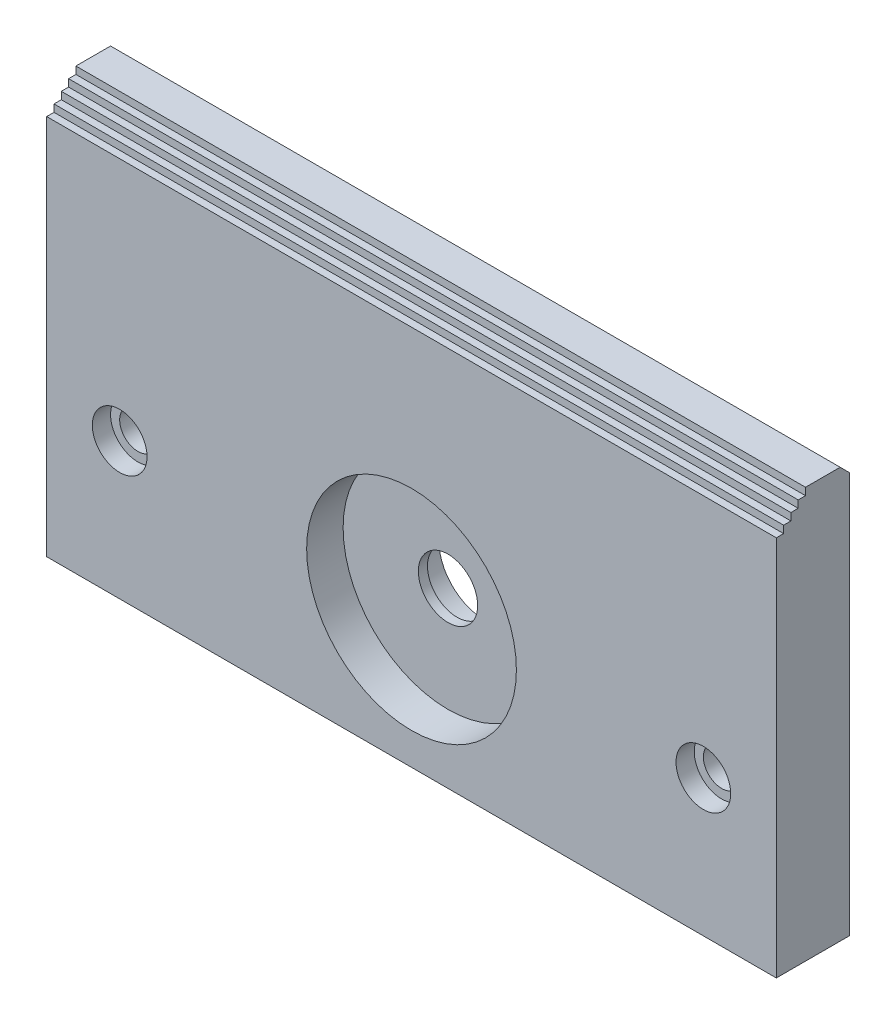
SolidWorks part; units mm, degrees
ref_plane "前视基准面" through (0, 0, 0) normal (0, 0, 1) x (1, 0, 0)
ref_plane "上视基准面" through (0, 0, 0) normal (0, 1, 0) x (1, 0, 0)
ref_plane "右视基准面" through (0, 0, 0) normal (1, 0, 0) x (0, 0, -1)
other "Configuration Table"
ref_plane "基准面1" through (0, 0, 8) normal (0, 0, 1) x (1, 0, 0)
sketch "草图1" plane through (0, 0, 8) normal (0, 0, 1) x (1, 0, 0)
  line L0 (80, -19.1667) -> (80, 40.8333)
  line L1 (80, 40.8333) -> (0, 40.8333)
  line L2 (0, 40.8333) -> (0, -19.1667)
  line L3 (0, -19.1667) -> (80, -19.1667)
  dimension "D1" = 80
  dimension "D2" = 60
extrude "凸台-拉伸1" add sketch "草图1" against normal blind 8
hole_wizard "M3.5 六角头机械螺钉的柱形沉头孔1" positions "草图13" profile "草图12" counterbore size "M3.5" standard "ANSI Metric" end condition through all
sketch "草图13" plane through (0, 0, 8) normal (0, 0, 1) x (1, 0, 0)
  line L1 (0, 10.8333) -> (80, 10.8333) construction
  line L2 (0, 40.8333) -> (0, -19.1667) construction
  line L3 (80, -19.1667) -> (80, 40.8333) construction
  point P0 (8, 10.8333)
  point P1 (72, 10.8333)
  dimension "D1" = 8
  dimension "D2" = 8
sketch "草图12" plane through (8, 10.8333, 8) normal (1, 0, 0) x (0, -1, 0)
  line L0 (0, 0) -> (0, 8)
  line L1 (0, 8) -> (2, 8)
  line L3 (2, 8) -> (2, 2)
  line L4 (2, 2) -> (3, 2)
  line L5 (3, 2) -> (3, 0)
  line L7 (3, 0) -> (0, 0)
  line L11 (0, -6.35) -> (0, 107.95) construction
  dimension "通孔孔直径" = 4
  dimension "通孔孔深度" = 8
  dimension "柱形沉头孔直径" = 6
  dimension "柱形沉头孔深度" = 2
sketch "草图14" plane through (0, 0, 8) normal (0, 0, 1) x (1, 0, 0)
  line L0 (40, 40.8333) -> (40, -19.1667) construction
  line L1 (80, 40.8333) -> (0, 40.8333) construction
  line L2 (0, -19.1667) -> (80, -19.1667) construction
  line L3 (0, 40.8333) -> (0, -19.1667) construction
  line L4 (0, 38.8333) -> (80, 38.8333)
  line L5 (0, 38.8333) -> (0, 36.8333)
  line L6 (0, 36.8333) -> (80, 36.8333)
  line L7 (40, 38.8333) -> (40, 36.8333)
  line L8 (80, -19.1667) -> (80, 40.8333) construction
  line L9 (15, 40.8333) -> (31, 24.8333)
  line L10 (6, 40.8333) -> (8, 40.8333)
  line L11 (6, 40.8333) -> (6, 24.8333)
  line L12 (6, 24.8333) -> (8, 24.8333)
  line L13 (8, 40.8333) -> (8, 24.8333)
  line L18 (39, 40.8333) -> (41, 40.8333)
  line L19 (39, 40.8333) -> (39, 24.8333)
  line L20 (39, 24.8333) -> (41, 24.8333)
  line L21 (40, 40.8333) -> (40, 24.8333)
  line L22 (31, 24.8333) -> (32.4142, 26.2475)
  line L23 (32.4142, 26.2475) -> (16.4142, 42.2475)
  line L24 (16.4142, 42.2475) -> (15, 40.8333)
  line L25 (0, 24.8333) -> (80, 24.8333) construction
  line L26 (74, 24.8333) -> (72, 24.8333)
  line L27 (72, 40.8333) -> (72, 24.8333)
  line L28 (74, 40.8333) -> (72, 40.8333)
  line L29 (74, 40.8333) -> (74, 24.8333)
  line L30 (47.5858, 26.2475) -> (63.5858, 42.2475)
  line L31 (49, 24.8333) -> (47.5858, 26.2475)
  line L32 (65, 40.8333) -> (49, 24.8333)
  line L33 (63.5858, 42.2475) -> (65, 40.8333)
  line L34 (41, 40.8333) -> (41, 24.8333)
  line L35 (80, 38.8333) -> (80, 36.8333)
  dimension "D1" = 2
  dimension "D2" = 2
  dimension "D3" = 6
  dimension "D4" = 2
  dimension "D5" = 16
  dimension "D6" = 2
  dimension "D7" = 1
  dimension "D8" = 7
  dimension "D9" = 45
extrude "切除-拉伸1" cut sketch "草图14" against normal blind 1 contours L4 L35 L6 L5 | L13 L12 L11 L10 | L9 L22 L23 L24 | L19 L20 L34 L18 | L30 L33 L32 L31 | L27 L26 L29 L28
sketch "草图15" plane through (0, 0, 8) normal (0, 0, 1) x (1, 0, 0)
  line L0 (40, 40.8333) -> (40, -19.1667) construction
  line L1 (39, 40.8333) -> (41, 40.8333) construction
  line L2 (0, -19.1667) -> (80, -19.1667) construction
  circle A0 centre (40, 10.8333) radius 3.25
  point P9 (40, 10.8333)
  dimension "D1" = 6.5
extrude "切除-拉伸2" cut sketch "草图15" against normal up to next
sketch "草图17" plane through (0, 0, 8) normal (0, 0, 1) x (1, 0, 0)
  circle A0 centre (40, 10.8333) radius 11.5
  dimension "D1" = 23
extrude "切除-拉伸4" cut sketch "草图17" against normal blind 4
sketch "草图18" plane through (0, 0, 0) normal (0, 0, -1) x (-1, 0, 0)
  circle A0 centre (-40, 10.8333) radius 5
  dimension "D1" = 10
extrude "切除-拉伸5" cut sketch "草图18" against normal blind 3
chamfer "倒角1" distance 1.5 angle 45 2 edges at (74, 10.8333, 0) (10, 10.8333, 0)
chamfer "倒角2" distance 1 angle 45 1 edges at (40, 40.8333, 0)
sketch "草图20" plane through (0, 0, 8) normal (0, 0, 1) x (1, 0, 0)
  line L0 (80, -19.1667) -> (80, 36.8333) construction
  line L1 (0, -19.1667) -> (80, -19.1667)
  line L2 (0, -19.1667) -> (0, -13.1667)
  line L3 (0, -13.1667) -> (80, -13.1667)
  line L4 (80, -19.1667) -> (80, -13.1667)
  dimension "D1" = 6
extrude "切除-拉伸6" cut sketch "草图20" against normal blind 1
sketch "草图21" plane through (0, 0, 7) normal (0, 0, 1) x (1, 0, 0)
  line L0 (80, -19.1667) -> (80, -13.1667) construction
  line L1 (0, -19.1667) -> (80, -19.1667)
  line L2 (0, -19.1667) -> (0, -15.1667)
  line L3 (0, -15.1667) -> (80, -15.1667)
  line L4 (80, -19.1667) -> (80, -15.1667)
  dimension "D1" = 4
extrude "切除-拉伸7" cut sketch "草图21" against normal blind 1
sketch "草图22" plane through (0, 0, 6) normal (0, 0, 1) x (1, 0, 0)
  line L1 (0, -19.1667) -> (80, -19.1667)
  line L2 (0, -19.1667) -> (0, -17.1667)
  line L3 (0, -17.1667) -> (80, -17.1667)
  line L4 (80, -19.1667) -> (80, -17.1667)
  dimension "D1" = 2
extrude "切除-拉伸8" cut sketch "草图22" against normal blind 1
sketch "草图23" plane through (0, 0, 8) normal (0, 0, 1) x (1, 0, 0)
  line L0 (6, 24.8333) -> (8, 24.8333) construction
  line L1 (31, 24.8333) -> (32.4142, 26.2475) construction
  line L2 (39, 24.8333) -> (41, 24.8333) construction
  line L3 (49, 24.8333) -> (47.5858, 26.2475) construction
  line L4 (74, 24.8333) -> (72, 24.8333) construction
  circle A0 centre (7, 24.8333) radius 1
  circle A1 centre (31.7071, 25.5404) radius 1
  circle A2 centre (40, 24.8333) radius 1
  circle A3 centre (48.2929, 25.5404) radius 1
  circle A4 centre (73, 24.8333) radius 1
extrude "切除-拉伸9" cut sketch "草图23" against normal up to surface (1 mm away) up to face at (40, 35.6249, 7)
sketch "草图24" plane through (0, 0, 8) normal (0, 0, 1) x (1, 0, 0)
  line L0 (0, 36.8333) -> (0, -13.1667) construction
  line L1 (0, -4.1667) -> (80, -4.1667)
  line L2 (0, -4.1667) -> (0, -19.1667)
  line L3 (0, -19.1667) -> (80, -19.1667)
  line L4 (80, -4.1667) -> (80, -19.1667)
  dimension "D1" = 15
extrude "切除-拉伸10" cut sketch "草图24" against normal up to next
sketch "草图25" plane through (0, 0, 8) normal (0, 0, 1) x (1, 0, 0)
  line L0 (80, -4.1667) -> (80, 36.8333) construction
  line L1 (0, 40.8333) -> (80, 40.8333)
  line L2 (0, 40.8333) -> (0, 22.8333)
  line L3 (0, 22.8333) -> (80, 22.8333)
  line L4 (80, 40.8333) -> (80, 22.8333)
  line L5 (0, 36.8333) -> (0, -4.1667) construction
  dimension "D1" = 18
extrude "凸台-拉伸2" add sketch "草图25" against normal blind 3
sketch "草图26" plane through (0, 0, 0) normal (-1, 0, 0) x (0, 0, 1)
  line L0 (4.8, 40.8333) -> (4.8, 40.0333)
  line L1 (1, 40.8333) -> (8, 40.8333) construction
  line L2 (4.8, 40.0333) -> (5.6, 40.0333)
  line L3 (5.6, 40.0333) -> (5.6, 39.2333)
  line L4 (5.6, 39.2333) -> (6.4, 39.2333)
  line L5 (6.4, 39.2333) -> (6.4, 38.4333)
  line L6 (6.4, 38.4333) -> (7.2, 38.4333)
  line L7 (7.2, 38.4333) -> (7.2, 37.6333)
  line L8 (7.2, 37.6333) -> (8, 37.6333)
  line L9 (8, 40.8333) -> (8, -4.1667) construction
  line L10 (8, 37.6333) -> (8, 40.8333)
  line L11 (8, 40.8333) -> (4.8, 40.8333)
  dimension "D1" = 0.8
  dimension "D2" = 0.8
  dimension "D3" = 0.8
  dimension "D4" = 0.8
  dimension "D5" = 0.8
  dimension "D6" = 0.8
  dimension "D7" = 0.8
  dimension "D8" = 0.8
extrude "切除-拉伸11" cut sketch "草图26" against normal up to next
